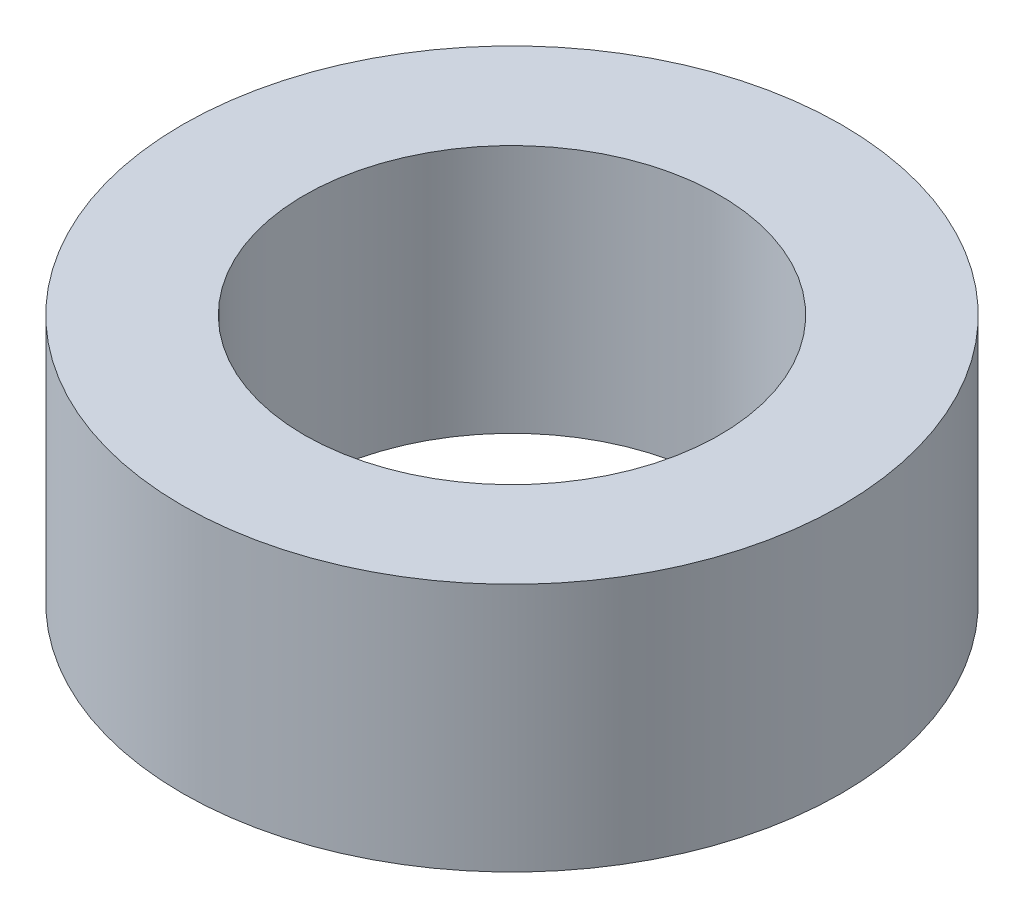
SolidWorks part; units mm, degrees
ref_plane "Front Plane" through (0, 0, 0) normal (0, 0, 1) x (1, 0, 0)
ref_plane "Top Plane" through (0, 0, 0) normal (0, 1, 0) x (1, 0, 0)
ref_plane "Right Plane" through (0, 0, 0) normal (1, 0, 0) x (0, 0, -1)
sketch "Sketch1" plane through (0, 0, 0) normal (0, 1, 0) x (1, 0, 0)
  circle A0 centre (0, 0) radius 6.35
  dimension "D1" = 12.7
extrude "Boss-Extrude1" add sketch "Sketch1" along normal blind 4.8
sketch "Sketch2" plane through (0, 4.8, 0) normal (0, 1, 0) x (1, 0, 0)
  circle A0 centre (0, 0) radius 4
  dimension "D1" = 8
sketch "Sketch3" plane through (0, 4.8, 0) normal (0, 1, 0) x (1, 0, 0)
  circle A0 centre (0, 0) radius 4
  dimension "D1" = 8
extrude "Cut-Extrude2" cut sketch "Sketch3" against normal through all
